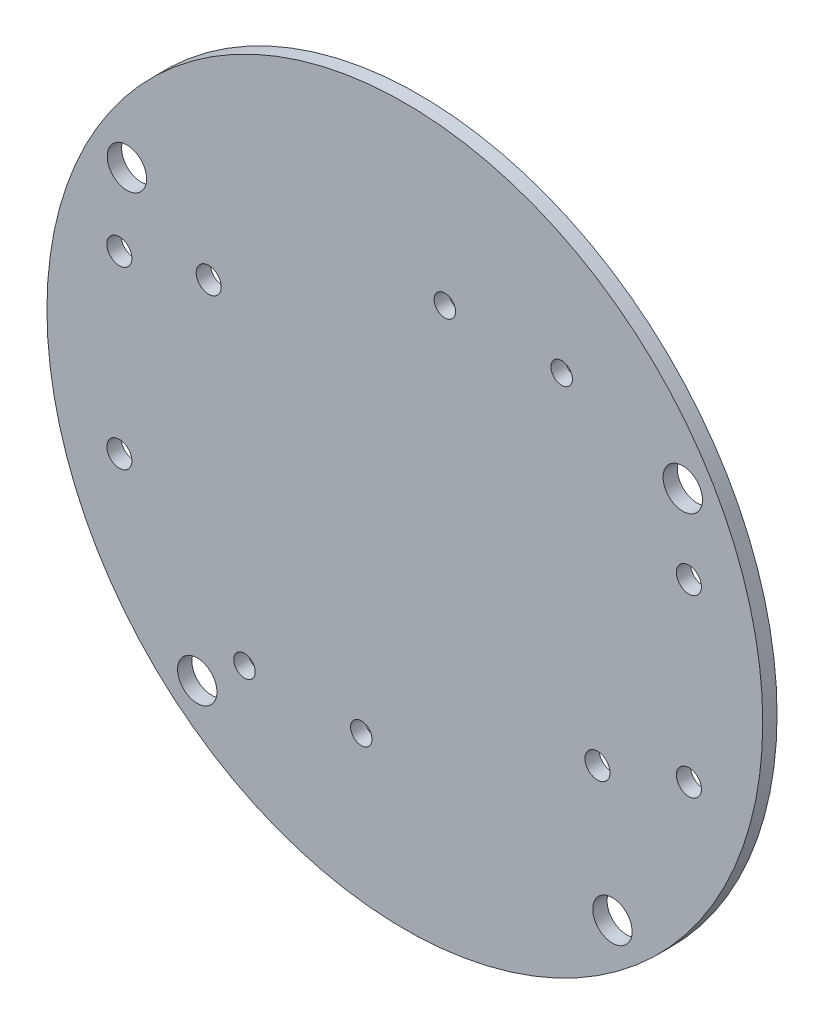
SolidWorks part; units mm, degrees
ref_plane "Plano frontal" through (0, 0, 0) normal (0, 0, 1) x (1, 0, 0)
ref_plane "Plano superior" through (0, 0, 0) normal (0, 1, 0) x (1, 0, 0)
ref_plane "Plano direito" through (0, 0, 0) normal (1, 0, 0) x (0, 0, -1)
sketch "Esboço1" plane through (0, 0, 0) normal (0, 0, 1) x (1, 0, 0)
  circle A0 centre (0, 0) radius 50
  dimension "D1" = 100
extrude "Ressalto-extrusão1" add sketch "Esboço1" along normal blind 2
sketch "Esboço2" plane through (0, 0, 2) normal (0, 0, 1) x (1, 0, 0)
  line L0 (0, 0) -> (0, 68.6386) construction
  line L1 (-61.9657, 0) -> (66.0984, 0) construction
  line L2 (-61.9657, -34.4093) -> (66.0984, -34.4093) construction
  line L3 (-65.4234, 22.88) -> (52.1255, 22.88) construction
  circle A4 centre (-29, -34.4093) radius 2.75
  circle A5 centre (29, -34.4093) radius 2.75
  circle A6 centre (-38.8242, 22.7526) radius 2.75
  circle A7 centre (38.8242, 22.7526) radius 2.75
  point P9 (2.9328, -3.8481)
  dimension "D1" = 58
  dimension "D4" = 45
  dimension "D2" = 45
  dimension "D8" = 5.5
  dimension "D9" = 5.5
  dimension "D10" = 5.5
  dimension "D11" = 5.5
  dimension "D3" = 45
  dimension "D5" = 45
  dimension "D6" = 58
  dimension "D7" = 58
extrude "Corte-extrusão1" cut sketch "Esboço2" against normal blind 2
sketch "Esboço3" plane through (0, 0, 2) normal (0, 0, 1) x (1, 0, 0)
  line L0 (71.0424, 0) -> (-71.0424, 0) construction
  line L1 (0, -53.8288) -> (0, 53.8288) construction
  circle A0 centre (-27.4, 14.89) radius 1.75
  circle A1 centre (26.91, -16.73) radius 1.75
  circle A2 centre (-39.88, -12.4) radius 1.75
  circle A3 centre (-39.88, 12.11) radius 1.75
  circle A4 centre (39.68, 12.16) radius 1.75
  circle A5 centre (39.68, -12.34) radius 1.75
  circle A6 centre (5.59, 28.28) radius 1.5
  circle A7 centre (21.91, 28.28) radius 1.5
  circle A8 centre (-6.08, -29.3) radius 1.5
  circle A9 centre (-22.4, -29.3) radius 1.5
  point P3 (0, 0)
  point P4 (0, 0)
  point P8 (0, 0)
  dimension "D1" = 3.5
  dimension "D6" = 12.11
  dimension "D14" = 28.28
  dimension "D22" = 3
  dimension "D23" = 3
  dimension "D24" = 3
  dimension "D25" = 3
  dimension "D2" = 27.4
  dimension "D3" = 14.89
  dimension "D4" = 26.91
  dimension "D5" = 16.73
  dimension "D7" = 12.4
  dimension "D8" = 39.88
  dimension "D9" = 39.88
  dimension "D10" = 12.34
  dimension "D11" = 12.16
  dimension "D12" = 39.68
  dimension "D13" = 39.68
  dimension "D15" = 28.28
  dimension "D16" = 5.59
  dimension "D17" = 21.91
  dimension "D18" = 29.3
  dimension "D19" = 29.3
  dimension "D20" = 6.08
  dimension "D21" = 22.4
extrude "Corte-extrusão2" cut sketch "Esboço3" against normal blind 10
